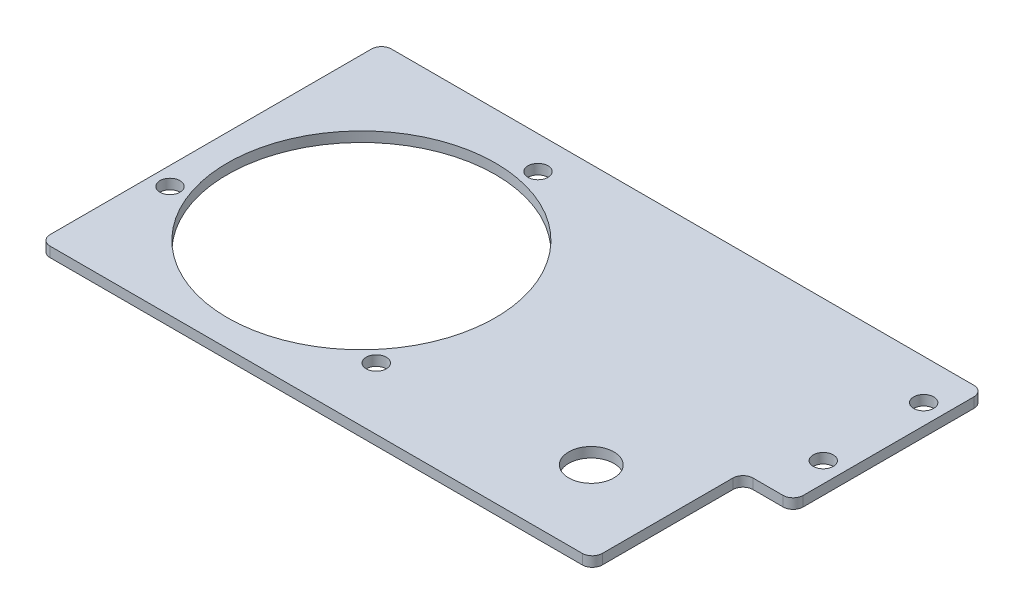
SolidWorks part; units mm, degrees
ref_plane "Front Plane" through (0, 0, 0) normal (0, 0, 1) x (1, 0, 0)
ref_plane "Top Plane" through (0, 0, 0) normal (0, 1, 0) x (1, 0, 0)
ref_plane "Right Plane" through (0, 0, 0) normal (1, 0, 0) x (0, 0, -1)
sketch "Sketch1" plane through (0, 0, 0) normal (0, 1, 0) x (1, 0, 0)
  line L0 (0, 114.3) -> (0, -101.6) construction
  line L1 (273.05, 114.3) -> (-95.25, 114.3)
  line L2 (279.4, 107.95) -> (279.4, 0)
  line L3 (241.3, -101.6) -> (-95.25, -101.6)
  line L4 (-101.6, 107.95) -> (-101.6, -95.25)
  line L5 (254, -6.35) -> (273.05, -6.35)
  line L6 (266.7, 0) -> (266.7, 114.3) construction
  line L7 (-101.6, 0) -> (285.75, 0) construction
  line L8 (0, 0) -> (-101.6, -34.9837) construction
  line L11 (247.65, -95.25) -> (247.65, -12.7)
  circle A0 centre (0, 0) radius 84.7725
  circle A1 centre (0, 0) radius 95.25 construction
  circle A2 centre (-90.0606, -31.0104) radius 6.35
  arc A3 (247.65, -12.7) -> (254, -6.35) centre (254, -12.7) cw
  arc A4 (-95.25, 114.3) -> (-101.6, 107.95) centre (-95.25, 107.95) ccw
  circle A5 centre (18.1746, 93.5) radius 6.35
  circle A6 centre (71.8861, -62.4896) radius 6.35
  arc A7 (-95.25, -101.6) -> (-101.6, -95.25) centre (-95.25, -95.25) cw
  arc A8 (241.3, -101.6) -> (247.65, -95.25) centre (241.3, -95.25) ccw
  arc A9 (273.05, -6.35) -> (279.4, 0) centre (273.05, 0) ccw
  arc A10 (273.05, 114.3) -> (279.4, 107.95) centre (273.05, 107.95) cw
  circle A11 centre (266.7, 88.9) radius 6.35
  circle A12 centre (266.7, 25.4) radius 6.35
  point P0 (0, 0)
  point P11 (0, 0)
  point P21 (247.65, -6.35)
  point P32 (247.65, -101.6)
  point P46 (0, 0)
  dimension "D3" = 169.545
  dimension "D5" = 190.5
  dimension "D6" = 12.7
  dimension "D7" = 114.3
  dimension "D8" = 279.4
  dimension "D11" = 6.35
  dimension "D14" = 12.7
  dimension "D1" = 101.6
  dimension "D2" = 101.6
  dimension "D4" = 19
  dimension "D9" = 95.25
  dimension "D10" = 31.75
  dimension "D13" = 12.7
  dimension "D15" = 25.4
extrude "Boss-Extrude1" add sketch "Sketch1" along normal blind 6.35
sketch "Sketch2" plane through (0, 0, 0) normal (0, -1, 0) x (1, 0, 0)
  line L0 (-101.6, -107.95) -> (-101.6, 95.25) construction
  line L1 (273.05, -114.3) -> (-95.25, -114.3) construction
  line L2 (279.4, 0) -> (279.4, -107.95) construction
  line L3 (-95.25, 101.6) -> (241.3, 101.6) construction
  line L4 (-101.6, -107.95) -> (-101.6, 95.25)
  line L5 (273.05, -114.3) -> (-95.25, -114.3)
  line L6 (279.4, 0) -> (279.4, -107.95)
  line L7 (-95.25, 101.6) -> (241.3, 101.6)
  line L8 (88.9, -114.3) -> (88.9, 101.6) construction
  line L9 (-101.6, -6.35) -> (279.4, -6.35) construction
  line L11 (333.375, 146.05) -> (-155.575, 146.05)
  line L12 (333.375, 146.05) -> (333.375, -158.75)
  line L13 (333.375, -158.75) -> (-155.575, -158.75)
  line L14 (-155.575, 146.05) -> (-155.575, -158.75)
  line L15 (333.375, 146.05) -> (-155.575, -158.75) construction
  line L16 (333.375, -158.75) -> (-155.575, 146.05) construction
  point P12 (88.9, -6.35)
  dimension "D1" = 381
  dimension "D2" = 215.9
  dimension "D3" = 488.95
  dimension "D4" = 304.8
sketch "Sketch3" plane through (0, 6.35, 0) normal (0, 1, 0) x (1, 0, 0)
  circle A0 centre (0, 0) radius 84.7725 construction
  point P0 (84.7725, 0)
sketch "Sketch4" plane through (0, 6.35, 0) normal (0, 1, 0) x (1, 0, 0)
  circle A0 centre (195.6867, -50.292) radius 11.176 construction
  circle A1 centre (195.6867, -50.292) radius 11.176 construction
  circle A2 centre (195.6867, -50.292) radius 14.2875
  dimension "D1" = 28.575
extrude "Cut-Extrude1" cut sketch "Sketch4" against normal blind 9.652
